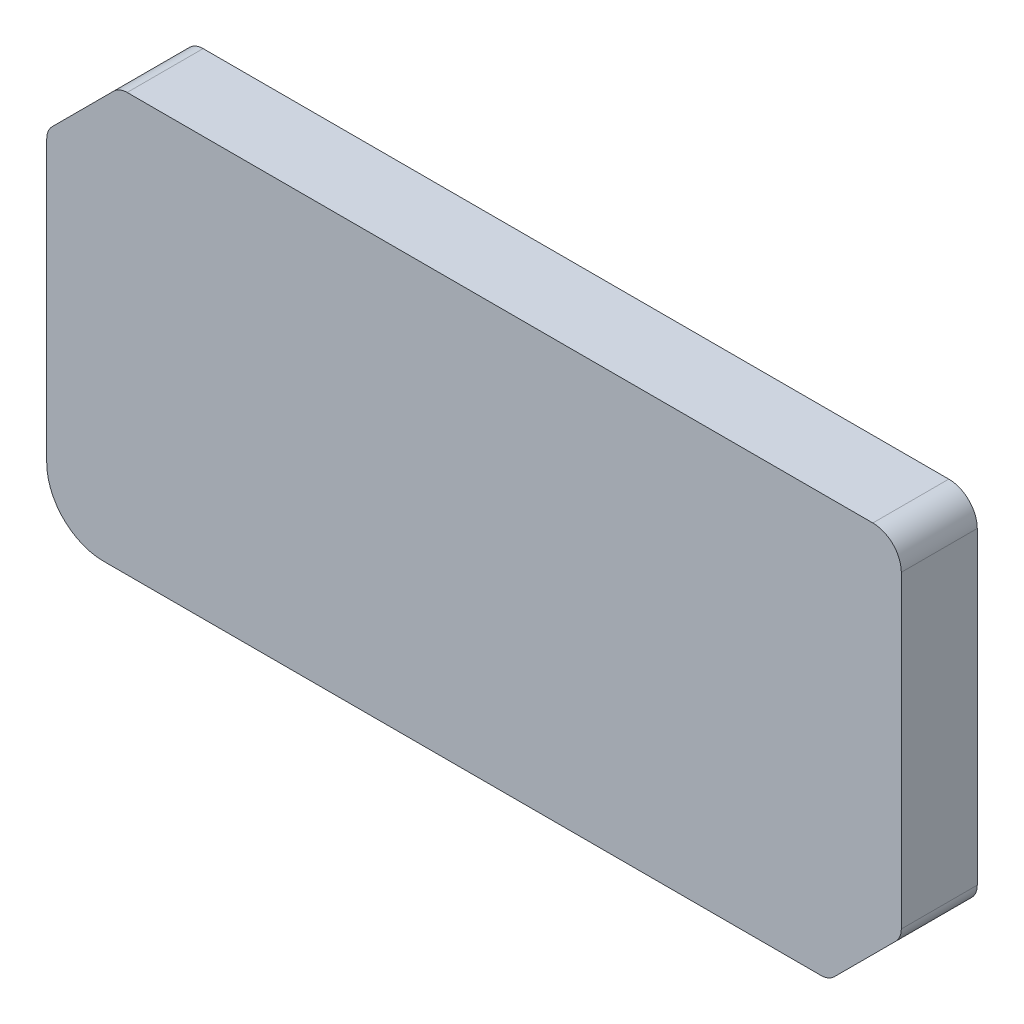
SolidWorks part; units mm, degrees
material "moto_black"
ref_plane "Front Plane" through (0, 0, 0) normal (0, 0, 1) x (1, 0, 0)
ref_plane "Top Plane" through (0, 0, 0) normal (0, 1, 0) x (1, 0, 0)
ref_plane "Right Plane" through (0, 0, 0) normal (1, 0, 0) x (0, 0, -1)
sketch "Sketch1" plane through (0, 0, 0) normal (0, 0, 1) x (1, 0, 0)
  line L1 (-112.5, -55) -> (112.5, -55)
  line L2 (-112.5, -55) -> (-112.5, 55)
  line L3 (-112.5, 55) -> (112.5, 55)
  line L4 (112.5, -55) -> (112.5, 55)
  line L5 (-112.5, -55) -> (112.5, 55) construction
  line L6 (-112.5, 55) -> (112.5, -55) construction
  point P0 (0, 0)
  dimension "D1" = 225
  dimension "D2" = 110
extrude "Boss-Extrude2" add sketch "Sketch1" along normal blind 10
chamfer "Chamfer1" distance 19.1 angle 45 2 edges at (112.5, -55, 5) (-112.5, 55, 5)
fillet "Fillet1" radius 15 1 edges at (-112.5, -55, 5)
fillet "Fillet2" radius 7.5 1 edges at (112.5, 55, 5)
fillet "Fillet3" radius 5 4 edges at (93.4, -55, 5) (112.5, -35.9, 5) (-112.5, 35.9, 5) (-93.4, 55, 5)
sketch "Sketch4" plane through (0, 0, 10) normal (0, 0, 1) x (1, 0, 0)
  line L6 (105, 55) -> (-91.3289, 55)
  line L7 (-94.8645, 53.5355) -> (-111.0355, 37.3645)
  line L8 (-112.5, 33.8289) -> (-112.5, -40)
  line L9 (-97.5, -55) -> (91.3289, -55)
  line L10 (94.8645, -53.5355) -> (111.0355, -37.3645)
  line L11 (112.5, -33.8289) -> (112.5, 47.5)
  line L12 (-97.5, -52) -> (91.3289, -52)
  line L13 (92.7431, -51.4142) -> (108.9142, -35.2431)
  line L14 (109.5, -33.8289) -> (109.5, 47.5)
  line L15 (105, 52) -> (-91.3289, 52)
  line L16 (-92.7431, 51.4142) -> (-108.9142, 35.2431)
  line L17 (-109.5, 33.8289) -> (-109.5, -40)
  line L18 (-97.5, -52) -> (91.3289, -52)
  line L19 (92.7431, -51.4142) -> (108.9142, -35.2431)
  line L20 (109.5, -33.8289) -> (109.5, 47.5)
  line L21 (105, 52) -> (-91.3289, 52)
  line L22 (-92.7431, 51.4142) -> (-108.9142, 35.2431)
  line L23 (-109.5, 33.8289) -> (-109.5, -40)
  line L24 (-66.9863, 52) -> (-66.9863, -52)
  line L25 (-109.5, 17) -> (-66.9863, 17)
  line L26 (-109.5, -18) -> (-66.9863, -18)
  line L27 (0, 0) -> (-55.0137, 0)
  line L28 (-109.5, 14) -> (-66.9863, 14)
  line L29 (-109.5, -21) -> (-66.9863, -21)
  line L30 (-63.9863, 52) -> (-63.9863, -52)
  arc A6 (-91.3289, 55) -> (-94.8645, 53.5355) centre (-91.3289, 50) ccw
  arc A7 (-111.0355, 37.3645) -> (-112.5, 33.8289) centre (-107.5, 33.8289) ccw
  arc A8 (-112.5, -40) -> (-97.5, -55) centre (-97.5, -40) ccw
  arc A9 (91.3289, -55) -> (94.8645, -53.5355) centre (91.3289, -50) ccw
  arc A10 (111.0355, -37.3645) -> (112.5, -33.8289) centre (107.5, -33.8289) ccw
  arc A11 (112.5, 47.5) -> (105, 55) centre (105, 47.5) ccw
  arc A12 (91.3289, -52) -> (92.7431, -51.4142) centre (91.3289, -50) ccw
  arc A13 (108.9142, -35.2431) -> (109.5, -33.8289) centre (107.5, -33.8289) ccw
  arc A14 (109.5, 47.5) -> (105, 52) centre (105, 47.5) ccw
  arc A15 (-91.3289, 52) -> (-92.7431, 51.4142) centre (-91.3289, 50) ccw
  arc A16 (-108.9142, 35.2431) -> (-109.5, 33.8289) centre (-107.5, 33.8289) ccw
  arc A17 (-109.5, -40) -> (-97.5, -52) centre (-97.5, -40) ccw
  arc A18 (91.3289, -52) -> (92.7431, -51.4142) centre (91.3289, -50) ccw
  arc A19 (108.9142, -35.2431) -> (109.5, -33.8289) centre (107.5, -33.8289) ccw
  arc A20 (109.5, 47.5) -> (105, 52) centre (105, 47.5) ccw
  arc A21 (-91.3289, 52) -> (-92.7431, 51.4142) centre (-91.3289, 50) ccw
  arc A22 (-108.9142, 35.2431) -> (-109.5, 33.8289) centre (-107.5, 33.8289) ccw
  arc A23 (-109.5, -40) -> (-97.5, -52) centre (-97.5, -40) ccw
  circle A24 centre (-17.263, 0) radius 35.7322
  circle A25 centre (57.3334, 22.8052) radius 18.5218
  circle A26 centre (57.3334, -22.8052) radius 18.5218
  circle A27 centre (-17.263, 0) radius 27.5379
  dimension "D3" = 35
  dimension "D4" = 35
  dimension "D1" = 3
  dimension "D2" = 3
  dimension "D5" = 3
  dimension "D6" = 3
extrude "Boss-Extrude4" add sketch "Sketch4" against normal blind 20
fillet "Fillet4" radius 2 3 edges at (75.8552, 22.8052, -10) (75.8552, -22.8052, -10) (18.4692, 0, -10)
fillet "Fillet5" radius 1 1 edges at (10.2749, 0, -10)
fillet "Fillet6" radius 1 3 edges at (-66.9863, -52, -5) (-66.9863, -21, -5) (-109.5, -21, -5)
fillet "Fillet7" radius 1 7 edges at (-109.5, 17, -5) (-66.9863, 52, -5) (-66.9863, 17, -5) (-109.5, 14, -5) (-66.9863, 14, -5) (-66.9863, -18, -5) (-109.5, -18, -5)
fillet "Fillet8" radius 1 10 edges at (-109.3478, 34.5943, -10) (-100.8287, 43.3287, -10) (-92.0943, 51.8478, -10) (-79.6576, 52, -10) (-67.2792, 51.7071, -10) (-66.9863, 34.5, -10) (-67.2792, 17.2929, -10) (-88.2431, 17, -10) (-109.2071, 17.2929, -10) (-109.5, 25.9145, -10)
fillet "Fillet9" radius 1 8 edges at (-109.2071, 13.7071, -10) (-109.5, -2, -10) (-109.2071, -17.7071, -10) (-88.2431, -18, -10) (-67.2792, -17.7071, -10) (-66.9863, -2, -10) (-67.2792, 13.7071, -10) (-88.2431, 14, -10)
fillet "Fillet10" radius 1 8 edges at (-109.2071, -21.2929, -10) (-88.2431, -21, -10) (-67.2792, -21.2929, -10) (-66.9863, -36.5, -10) (-67.2792, -51.7071, -10) (-82.7431, -52, -10) (-105.9853, -48.4853, -10) (-109.5, -31, -10)
